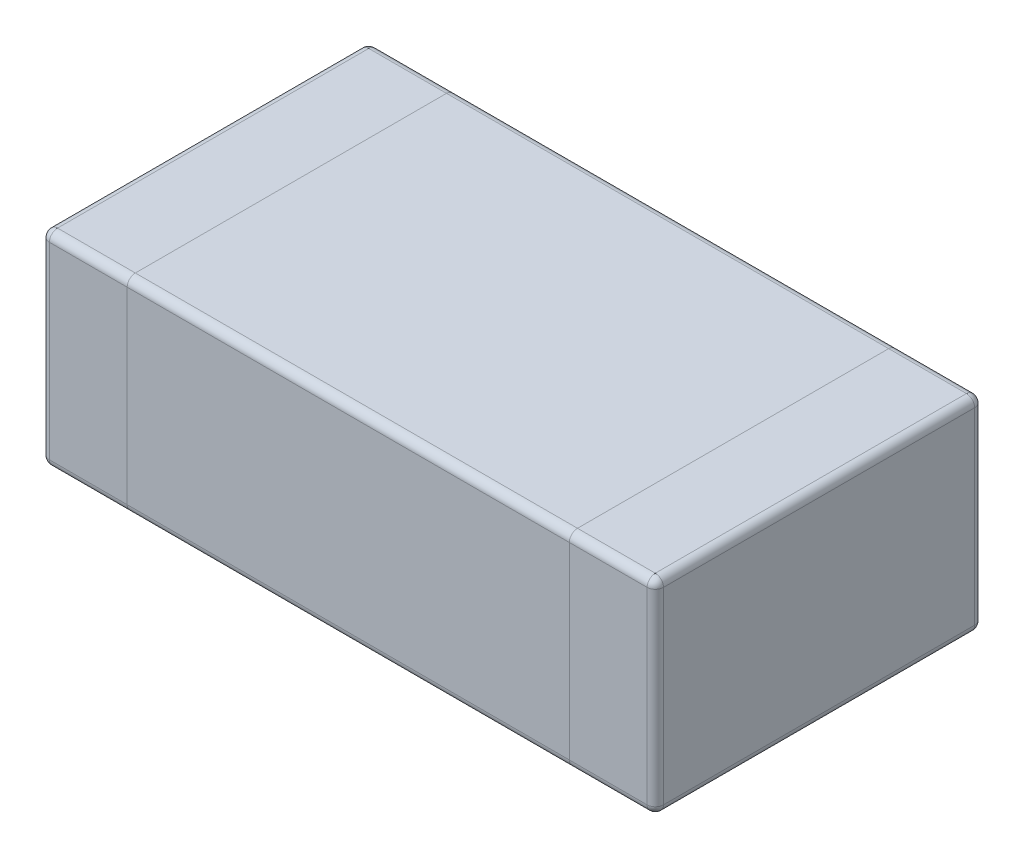
SolidWorks part; units mm, degrees
ref_plane "Front Plane" through (0, 0, 0) normal (0, 0, 1) x (1, 0, 0)
ref_plane "Top Plane" through (0, 0, 0) normal (0, 1, 0) x (1, 0, 0)
ref_plane "Right Plane" through (0, 0, 0) normal (1, 0, 0) x (0, 0, -1)
sketch "Sketch1" plane through (0, 0, 0) normal (0, 1, 0) x (1, 0, 0)
  line L1 (-0.73, -0.4) -> (0.73, -0.4)
  line L2 (-0.75, -0.38) -> (-0.75, 0.38)
  line L3 (-0.73, 0.4) -> (0.73, 0.4)
  line L4 (0.75, -0.38) -> (0.75, 0.38)
  line L5 (-0.75, -0.4) -> (0.75, 0.4) construction
  line L6 (-0.75, 0.4) -> (0.75, -0.4) construction
  arc A4 (-0.75, -0.38) -> (-0.73, -0.4) centre (-0.73, -0.38) ccw
  arc A5 (0.73, -0.4) -> (0.75, -0.38) centre (0.73, -0.38) ccw
  arc A6 (0.75, 0.38) -> (0.73, 0.4) centre (0.73, 0.38) ccw
  arc A7 (-0.73, 0.4) -> (-0.75, 0.38) centre (-0.73, 0.38) ccw
  point P0 (0, 0)
  dimension "D4" = 0.02
  dimension "D1" = 1.5
  dimension "D2" = 0.8
extrude "Boss-Extrude1" add sketch "Sketch1" along normal mid plane 0.5
sketch "Sketch3" plane through (0, 0.25, 0) normal (0, 1, 0) x (1, 0, 0)
  line L0 (-0.54, 0) -> (0.54, 0) construction
  line L1 (-0.54, -0.5133) -> (-0.54, 0.5133)
  line L2 (0.54, -0.5133) -> (0.54, 0.5133)
  line L3 (0, -0.145) -> (0, 0.145) construction
  line L6 (-0.54, -0.145) -> (0.54, -0.145) construction
  point P4 (0, 0)
  point P8 (-0.54, 0)
  point P11 (0.54, 0)
  point P14 (0, 0)
  point P17 (0, -0.145)
  dimension "D1" = 1.08
  dimension "D2" = 0.29
sketch "Sketch4" plane through (0, 0, 0.4) normal (0, 0, 1) x (1, 0, 0)
  line L0 (-0.54, 0.25) -> (-0.54, -0.5946)
  line L1 (0.54, 0.25) -> (0.54, -0.5946)
sketch "Sketch5" plane through (0, 0, -0.4) normal (0, 0, -1) x (-1, 0, 0)
  line L0 (-0.54, 0.25) -> (-0.54, -0.5946) construction
  line L1 (-0.54, 0.25) -> (-0.54, -0.5946)
  line L2 (0.54, 0.25) -> (0.54, -0.5946) construction
  line L3 (0.54, 0.25) -> (0.54, -0.5946)
sketch "Sketch6" plane through (0, -0.25, 0) normal (0, -1, 0) x (1, 0, 0)
  line L0 (0.54, 0.5133) -> (0.54, -0.5133) construction
  line L1 (-0.54, 0.5133) -> (-0.54, -0.5133) construction
  line L2 (0.54, 0.5133) -> (0.54, -0.5133)
  line L3 (-0.54, 0.5133) -> (-0.54, -0.5133)
split line "Split Line2"
split line "Split Line3"
split line "Split Line4"
split line "Split Line5"
fillet "Fillet2" radius 0.02 24 edges at (0.635, -0.25, 0.4) (-0.635, -0.25, 0.4) (0, -0.25, 0.4) (-0.7441, -0.25, 0.3941) (-0.75, -0.25, 0) (-0.7441, -0.25, -0.3941) (-0.635, -0.25, -0.4) (0.635, -0.25, -0.4) (0, -0.25, -0.4) (0.7441, -0.25, -0.3941) (0.75, -0.25, 0) (0.7441, -0.25, 0.3941) (-0.635, 0.25, -0.4) (0, 0.25, -0.4) (0.635, 0.25, -0.4) (0.7441, 0.25, -0.3941) (0.75, 0.25, 0) (0.7441, 0.25, 0.3941) (-0.635, 0.25, 0.4) (0, 0.25, 0.4) (0.635, 0.25, 0.4) (-0.7441, 0.25, 0.3941) (-0.75, 0.25, 0) (-0.7441, 0.25, -0.3941)
